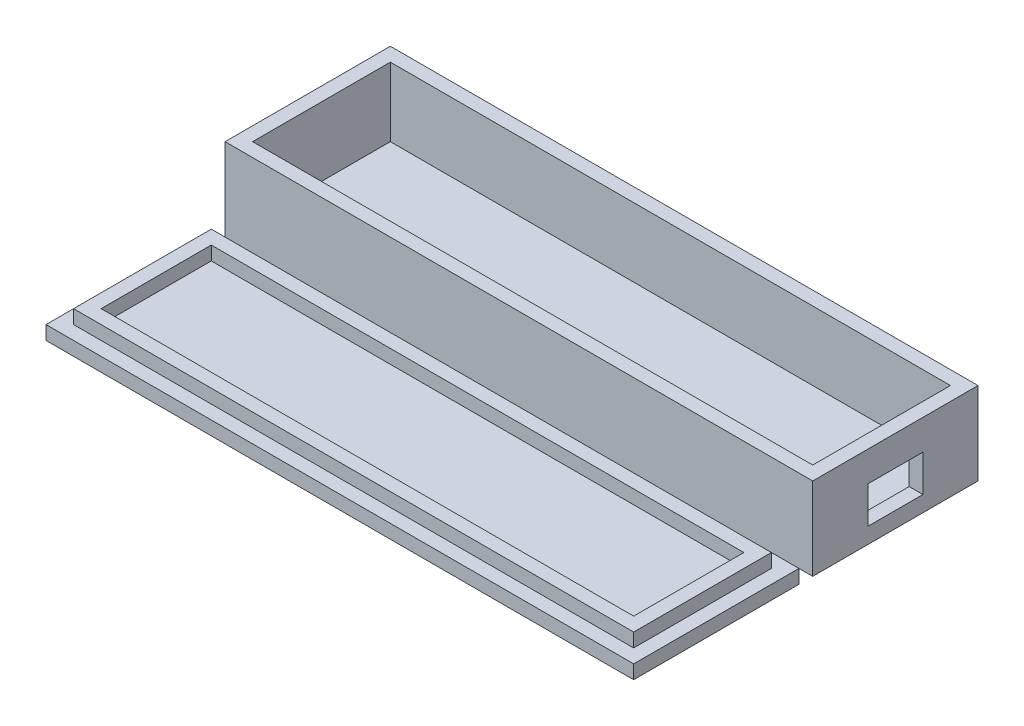
SolidWorks part; units mm, degrees
ref_plane "Alzado" through (0, 0, 0) normal (0, 0, 1) x (1, 0, 0)
ref_plane "Planta" through (0, 0, 0) normal (0, 1, 0) x (1, 0, 0)
ref_plane "Vista lateral" through (0, 0, 0) normal (1, 0, 0) x (0, 0, -1)
sketch "Croquis1" plane through (0, 0, 0) normal (0, 1, 0) x (1, 0, 0)
  line L0 (-67.1, 0) -> (67.1, 0) construction
  line L1 (-64, -18) -> (64, -18)
  line L2 (-64, -18) -> (-64, 18)
  line L3 (-64, 18) -> (64, 18)
  line L4 (64, -18) -> (64, 18)
  line L5 (0, -16.5) -> (0, 16.5) construction
  point P0 (0, 0)
  dimension "D1" = 128
  dimension "D2" = 36
  dimension "D3" = 18
  dimension "D4" = 64
extrude "Saliente-Extruir1" add sketch "Croquis1" along normal blind 3
sketch "Croquis3" plane through (0, 3, 0) normal (0, 1, 0) x (1, 0, 0)
  line L0 (64, 18) -> (-64, 18) construction
  line L1 (-61, -15) -> (61, -15)
  line L2 (-61, -15) -> (-61, 15)
  line L3 (-61, 15) -> (61, 15)
  line L4 (61, -15) -> (61, 15)
  line L5 (-61, -15) -> (61, 15) construction
  line L6 (-61, 15) -> (61, -15) construction
  line L7 (64, -18) -> (64, 18) construction
  line L9 (-64, -18) -> (64, -18)
  line L10 (-64, -18) -> (-64, 18)
  line L11 (-64, 18) -> (64, 18)
  line L12 (64, -18) -> (64, 18)
  line L13 (-64, -18) -> (64, 18) construction
  line L14 (-64, 18) -> (64, -18) construction
  point P0 (0, 0)
  point P10 (0, 0)
  dimension "D1" = 3
  dimension "D2" = 3
extrude "Saliente-Extruir2" add sketch "Croquis3" along normal blind 15
sketch "Croquis4" plane through (64, 0, 0) normal (1, 0, 0) x (0, 0, -1)
  line L0 (0, 1.65) -> (0, -1.65) construction
  line L1 (-6, 3.4384) -> (6, 3.4384)
  line L2 (-6, 3.4384) -> (-6, 11.4384)
  line L3 (-6, 11.4384) -> (6, 11.4384)
  line L4 (6, 3.4384) -> (6, 11.4384)
  line L5 (-6, 3.4384) -> (6, 11.4384) construction
  line L6 (-6, 11.4384) -> (6, 3.4384) construction
  point P0 (0, 7.4384)
  dimension "D1" = 12
  dimension "D2" = 8
extrude "Cortar-Extruir1" cut sketch "Croquis4" against normal blind 12
sketch "Croquis6" plane through (0, 0, 0) normal (0, 1, 0) x (1, 0, 0)
  line L0 (-64, 18) -> (-64, -18) construction
  line L1 (-64, -18) -> (64, -18) construction
  line L4 (-64, -57) -> (64, -57)
  line L5 (-64, -57) -> (-64, -21)
  line L6 (-64, -21) -> (64, -21)
  line L7 (64, -57) -> (64, -21)
  point P2 (5.2514, -43.4777)
  point P3 (0, -39)
  dimension "D1" = 0
  dimension "D3" = 36
  dimension "D4" = 128
  dimension "D5" = 3
extrude "Saliente-Extruir3" add sketch "Croquis6" along normal blind 3 separate body
sketch "Croquis7" plane through (0, 3, 0) normal (0, 1, 0) x (1, 0, 0)
  line L0 (0, -9.9) -> (0, 9.9) construction
  line L1 (-61, -54) -> (61, -54)
  line L2 (-61, -54) -> (-61, -24)
  line L3 (-61, -24) -> (61, -24)
  line L4 (61, -54) -> (61, -24)
  line L5 (-61, -54) -> (61, -24) construction
  line L6 (-61, -24) -> (61, -54) construction
  line L7 (64, -21) -> (-64, -21) construction
  line L8 (-64, -57) -> (64, -57) construction
  line L9 (-64, -21) -> (-64, -57) construction
  line L10 (-64, -57) -> (-64, -21)
  line L11 (-64, -21) -> (64, -21)
  line L16 (64, -57) -> (64, -21)
  line L17 (-64, -57) -> (64, -57)
  line L18 (-58, -27) -> (58, -27)
  line L19 (58, -51) -> (58, -27)
  line L20 (-58, -51) -> (58, -51)
  line L21 (-58, -51) -> (-58, -27)
  point P0 (0, -39)
  point P13 (0, -39)
  dimension "D1" = 3
  dimension "D2" = 3
  dimension "D3" = 3
  dimension "D4" = 3
  dimension "D5" = 3
extrude "Saliente-Extruir5" add sketch "Croquis7" along normal blind 3 contours L1 L4 L3 L2 L20 L21 L18 L19
